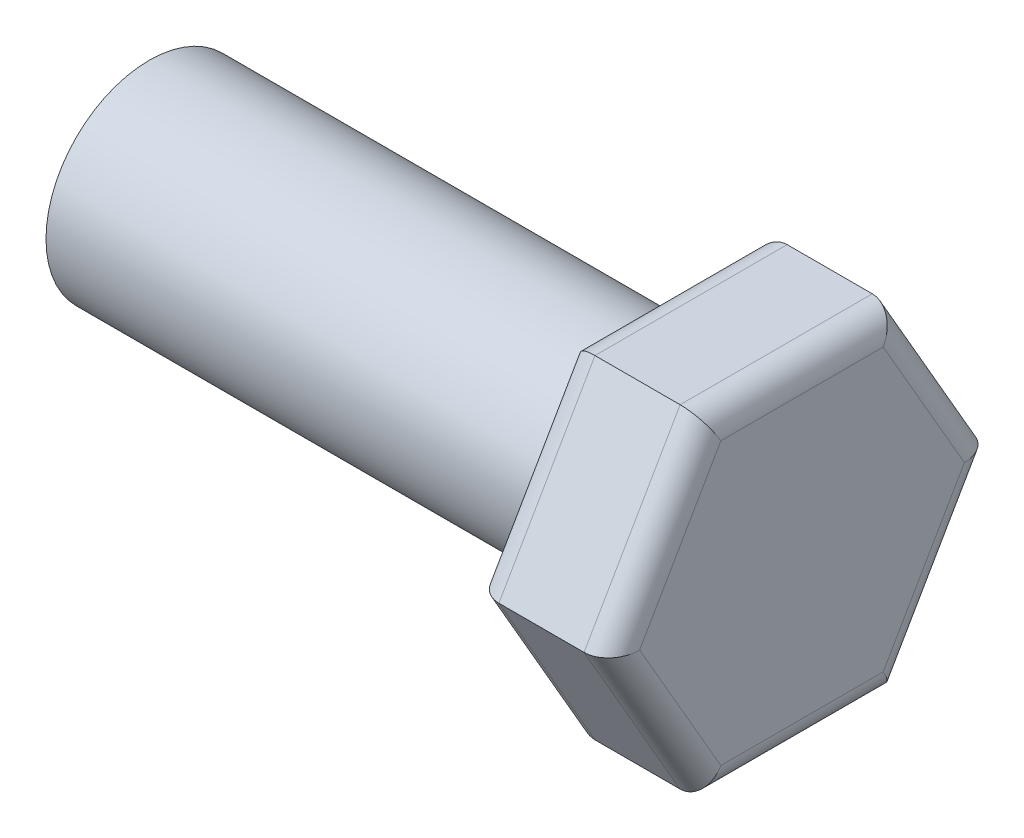
SolidWorks part; units mm, degrees
ref_plane "Front Plane" through (0, 0, 0) normal (0, 0, 1) x (1, 0, 0)
ref_plane "Top Plane" through (0, 0, 0) normal (0, 1, 0) x (1, 0, 0)
ref_plane "Right Plane" through (0, 0, 0) normal (1, 0, 0) x (0, 0, -1)
sketch "Sketch1" plane through (0, 0, 0) normal (1, 0, 0) x (0, 0, -1)
  line L1 (-3.7239, 6.45) -> (-7.4478, 0)
  line L2 (-7.4478, 0) -> (-3.7239, -6.45)
  line L3 (-3.7239, -6.45) -> (3.7239, -6.45)
  line L4 (3.7239, -6.45) -> (7.4478, 0)
  line L5 (7.4478, 0) -> (3.7239, 6.45)
  line L6 (3.7239, 6.45) -> (-3.7239, 6.45)
  circle A0 centre (0, 0) radius 6.45 construction
  dimension "D1" = 12.9
extrude "Boss-Extrude1" add sketch "Sketch1" along normal blind 5.3
sketch "Sketch2" plane through (0, 0, 0) normal (1, 0, 0) x (0, 0, -1)
  circle A0 centre (0, 0) radius 4
  dimension "D1" = 8
extrude "Boss-Extrude2" add sketch "Sketch2" against normal blind 20
thread "Thread1" pitch 1 start angle 0, offset 0, length 0, pitch 1, diameter 8
ref_plane "Plane1" through (-20, 0, -4) normal (0, -1, 0) x (0, 0, -1)
sketch "Thread Profile1" plane through (-20, 0, -4) normal (0, -1, 0) x (0, 0, -1)
  line L0 (0, 0) -> (0, 1) construction
  line L1 (0, 0) -> (0.5413, 0.3125)
  line L2 (0.5413, 0.3125) -> (0.5413, 0.4375)
  line L3 (0.5413, 0.4375) -> (0, 0.75)
  line L4 (0.5413, 0.375) -> (0, 0.375) construction
  line L11 (0, 0) -> (0, 0.75)
  point P2 (0, 0)
  dimension "Pitch" = 1
  dimension "Profile_Angle" = 60
  dimension "Profile_Land" = 0.125
  dimension "Profile_Height" = 0.5413
fillet "Fillet1" radius 1 12 edges at (0, 6.45, 0) (0, 3.225, 5.5859) (0, -3.225, 5.5859) (0, -6.45, 0) (0, 3.225, -5.5859) (0, -3.225, -5.5859) (5.3, -6.45, 0) (5.3, -3.225, 5.5859) (5.3, 3.225, 5.5859) (5.3, 6.45, 0) (5.3, 3.225, -5.5859) (5.3, -3.225, -5.5859)
